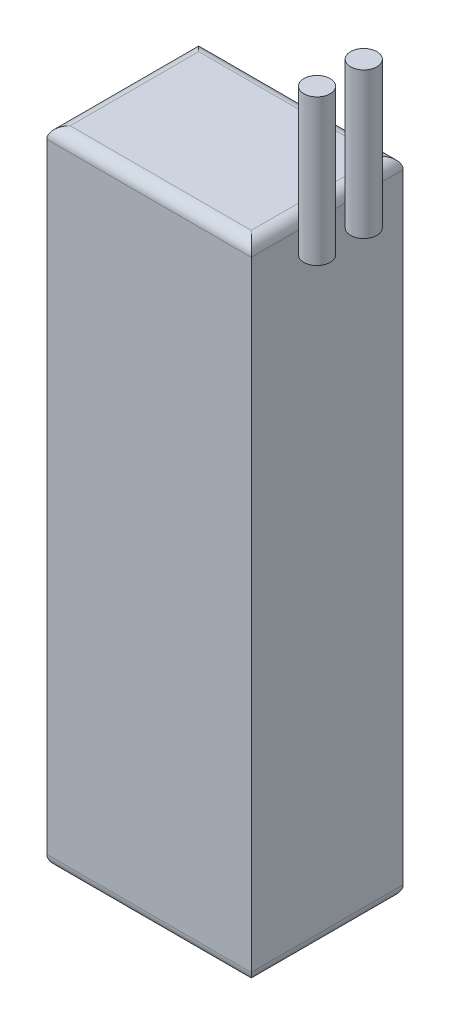
SolidWorks part; units mm, degrees
ref_plane "Front Plane" through (0, 0, 0) normal (0, 0, 1) x (1, 0, 0)
ref_plane "Top Plane" through (0, 0, 0) normal (0, 1, 0) x (1, 0, 0)
ref_plane "Right Plane" through (0, 0, 0) normal (1, 0, 0) x (0, 0, -1)
sketch "Sketch1" plane through (0, 0, 0) normal (0, 1, 0) x (1, 0, 0)
  line L1 (-17.5, 13) -> (17.5, 13)
  line L2 (-17.5, 13) -> (-17.5, -13)
  line L3 (-17.5, -13) -> (17.5, -13)
  line L4 (17.5, 13) -> (17.5, -13)
  line L5 (-17.5, 13) -> (17.5, -13) construction
  line L6 (-17.5, -13) -> (17.5, 13) construction
  point P0 (0, 0)
  dimension "D1" = 35
  dimension "D2" = 26
extrude "Boss-Extrude1" add sketch "Sketch1" along normal blind 110
sketch "Sketch2" plane through (0, 110, 0) normal (0, 1, 0) x (1, 0, 0)
  line L0 (0, 0) -> (29.1838, 0) construction
  line L1 (17.5, -13) -> (17.5, 13) construction
  circle A0 centre (19.75, 4) radius 2.25
  circle A1 centre (19.75, -4) radius 2.25
  point P5 (20.409, 3.0275)
  dimension "D1" = 4.5
  dimension "D2" = 8
extrude "Boss-Extrude2" add sketch "Sketch2" along normal blind 20 and the other way blind 5 separate body
fillet "Fillet1" radius 2 8 edges at (0, 110, 13) (-17.5, 110, 0) (0, 110, -13) (17.5, 110, 0) (0, 0, -13) (-17.5, 0, 0) (0, 0, 13) (17.5, 0, 0)
